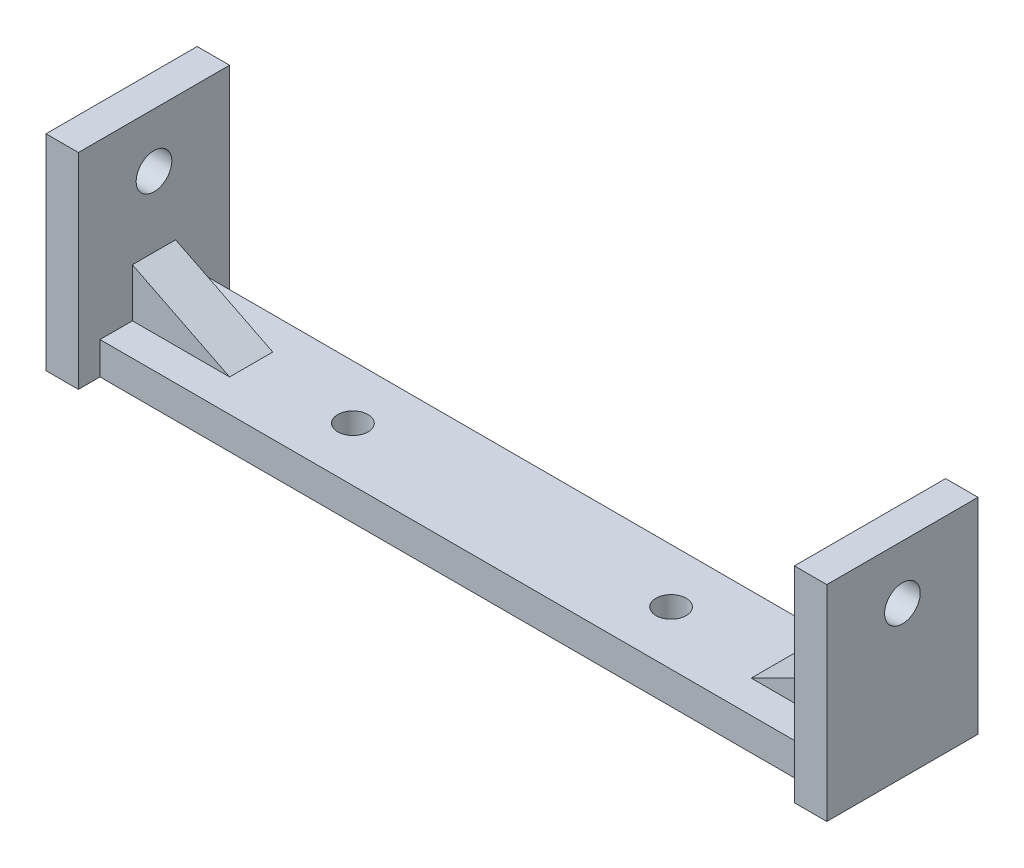
SolidWorks part; units mm, degrees
ref_plane "前视基准面" through (0, 0, 0) normal (0, 0, 1) x (1, 0, 0)
ref_plane "上视基准面" through (0, 0, 0) normal (0, 1, 0) x (1, 0, 0)
ref_plane "右视基准面" through (0, 0, 0) normal (1, 0, 0) x (0, 0, -1)
sketch "草图1" plane through (0, 0, 0) normal (0, 1, 0) x (1, 0, 0)
  line L1 (36.15, -5) -> (-36.15, -5)
  line L2 (36.15, -5) -> (36.15, 5)
  line L3 (36.15, 5) -> (-36.15, 5)
  line L4 (-36.15, -5) -> (-36.15, 5)
  line L5 (36.15, -5) -> (-36.15, 5) construction
  line L6 (36.15, 5) -> (-36.15, -5) construction
  circle A0 centre (-14.73, 0) radius 1.4
  circle A1 centre (14.73, 0) radius 1.4
  point P0 (0, 0)
  dimension "D3" = 2.8
  dimension "D4" = 14.73
  dimension "D5" = 2.8
  dimension "D6" = 29.46
  dimension "D1" = 10
  dimension "D2" = 72.3
extrude "凸台-拉伸1" add sketch "草图1" along normal blind 3
sketch "草图2" plane through (0, 0, 0) normal (0, 1, 0) x (1, 0, 0)
  line L0 (-36.15, 5) -> (-36.15, -5) construction
  line L1 (-36.15, -7) -> (-33.15, -7)
  line L2 (-36.15, -7) -> (-36.15, 7)
  line L3 (-36.15, 7) -> (-33.15, 7)
  line L4 (-33.15, -7) -> (-33.15, 7)
  line L10 (36.15, 5) -> (-36.15, 5) construction
  line L11 (-36.15, -5) -> (36.15, -5) construction
  line L12 (0, -55) -> (0, 55) construction
  line L13 (36.15, -7) -> (33.15, -7)
  line L14 (36.15, -7) -> (36.15, 7)
  line L15 (33.15, -7) -> (33.15, 7)
  line L16 (36.15, 7) -> (33.15, 7)
  dimension "D1" = 3
  dimension "D3" = 2
  dimension "D4" = 2
extrude "凸台-拉伸2" add sketch "草图2" along normal blind 19
sketch "草图3" plane through (-36.15, 0, 0) normal (-1, 0, 0) x (0, 0, 1)
  line L2 (7, 19) -> (7, 0) construction
  line L3 (-7, 19) -> (7, 19) construction
  circle A6 centre (0, 14) radius 1.65
  dimension "D1" = 7
  dimension "D2" = 5
  dimension "D9" = 3.3
extrude "切除-拉伸1" cut sketch "草图3" against normal up to surface (72.3 mm away) up to face at (36.15, 9.5, 0)
sketch "草图4" plane through (0, 0, 0) normal (0, 0, 1) x (1, 0, 0)
  line L3 (0, -7.7) -> (0, 7.7) construction
  line L4 (-36.15, 9) -> (-24.15, 3)
  line L5 (-36.15, 3) -> (-36.15, 9)
  line L6 (36.15, 9) -> (24.15, 3)
  line L7 (36.15, 3) -> (36.15, 9)
  line L8 (24.15, 3) -> (36.15, 3)
  line L9 (-24.15, 3) -> (-36.15, 3)
  dimension "D1" = 6
  dimension "D2" = 12
extrude "凸台-拉伸3" add sketch "草图4" along normal blind 2 and the other way blind 2
